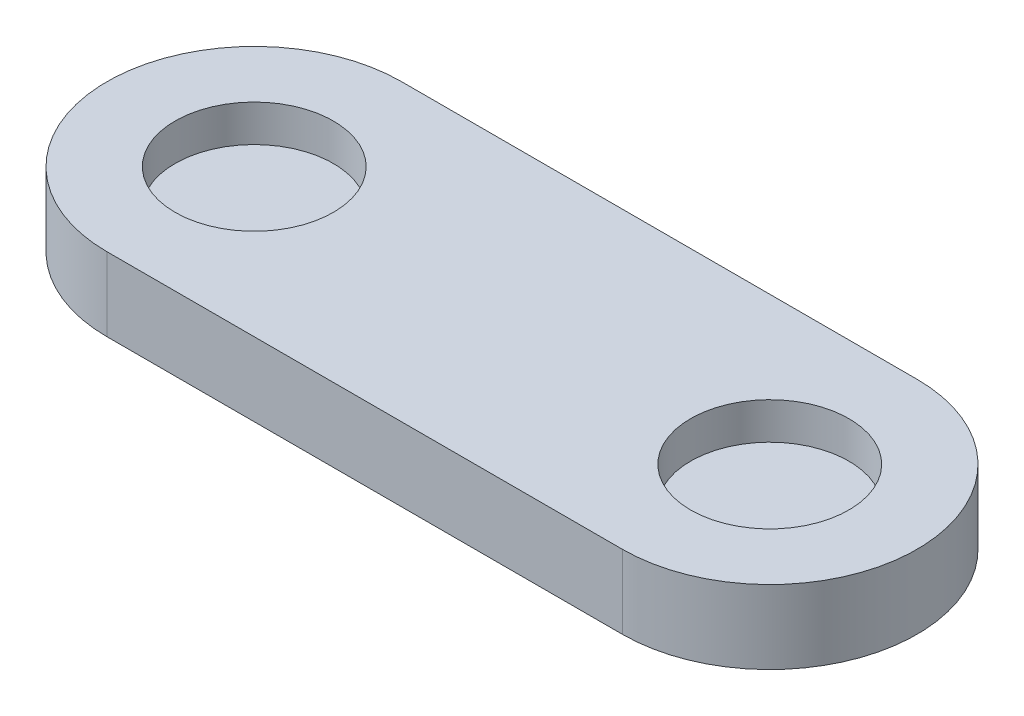
SolidWorks part; units mm, degrees
ref_plane "Front Plane" through (0, 0, 0) normal (0, 0, 1) x (1, 0, 0)
ref_plane "Top Plane" through (0, 0, 0) normal (0, 1, 0) x (1, 0, 0)
ref_plane "Right Plane" through (0, 0, 0) normal (1, 0, 0) x (0, 0, -1)
sketch "Sketch1" plane through (0, 0, 0) normal (0, 1, 0) x (1, 0, 0)
  line L0 (8.89, 0) -> (-8.89, 0) construction
  line L1 (8.89, -5.08) -> (-8.89, -5.08)
  line L2 (8.89, 5.08) -> (-8.89, 5.08)
  arc A0 (8.89, -5.08) -> (8.89, 5.08) centre (8.89, 0) ccw
  arc A1 (-8.89, 5.08) -> (-8.89, -5.08) centre (-8.89, 0) ccw
  circle A2 centre (-8.89, 0) radius 2.7305
  circle A3 centre (8.89, 0) radius 2.7305
  point P2 (0, 0)
  dimension "D3" = 5.461
  dimension "D1" = 17.78
  dimension "D2" = 10.16
extrude "Boss-Extrude1" add sketch "Sketch1" along normal blind 1.27
sketch "Sketch2" plane through (0, 0, 0) normal (0, -1, 0) x (1, 0, 0)
  line L2 (8.89, 5.08) -> (-8.89, 5.08)
  line L3 (-8.89, -5.08) -> (8.89, -5.08)
  line L4 (8.89, 5.08) -> (-8.89, 5.08)
  line L5 (-8.89, -5.08) -> (8.89, -5.08)
  arc A2 (8.89, -5.08) -> (8.89, 5.08) centre (8.89, 0) ccw
  arc A3 (-8.89, 5.08) -> (-8.89, -5.08) centre (-8.89, 0) ccw
  arc A4 (8.89, -5.08) -> (8.89, 5.08) centre (8.89, 0) ccw
  arc A5 (-8.89, 5.08) -> (-8.89, -5.08) centre (-8.89, 0) ccw
  dimension "D1" = 0
extrude "Boss-Extrude2" add sketch "Sketch2" along normal blind 1.27
